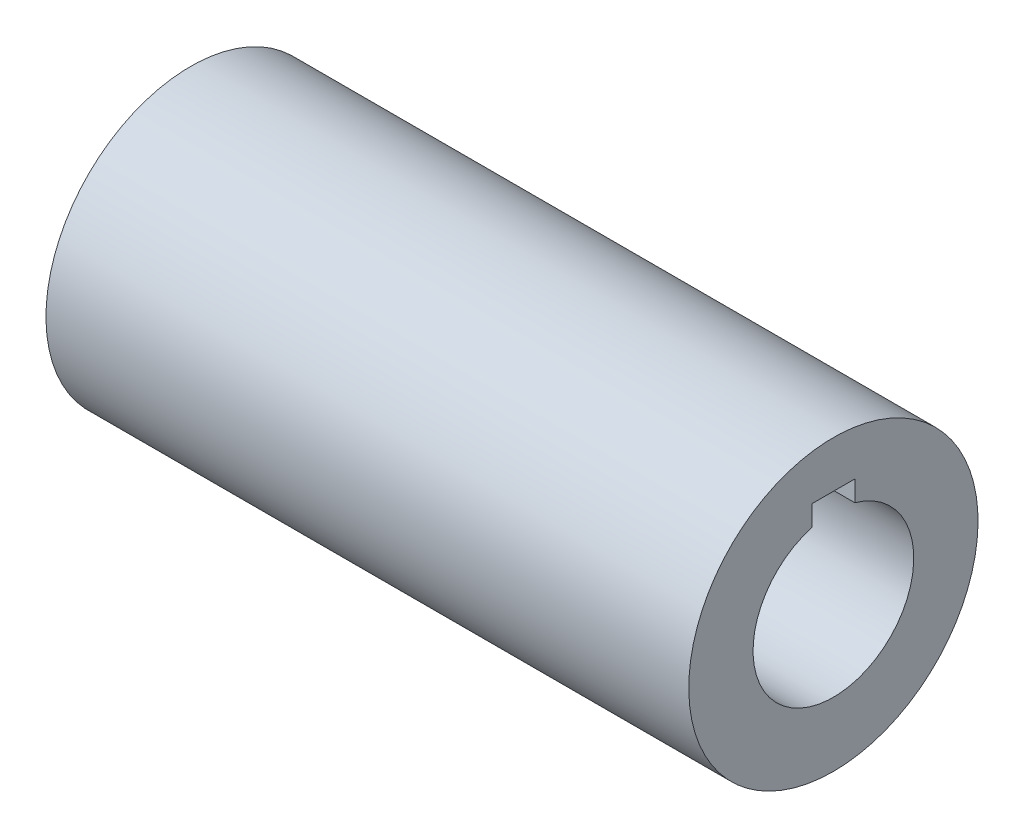
SolidWorks part; units mm, degrees
ref_plane "Ön Düzlem" through (0, 0, 0) normal (0, 0, 1) x (1, 0, 0)
ref_plane "Üst Düzlem" through (0, 0, 0) normal (0, 1, 0) x (1, 0, 0)
ref_plane "Sağ Düzlem" through (0, 0, 0) normal (1, 0, 0) x (0, 0, -1)
sketch "Sketch1" plane through (0, 0, 0) normal (0, 0, 1) x (1, 0, 0)
  line L0 (-60, 0) -> (60, 0) construction
  line L2 (-60, 15) -> (60, 15)
  line L3 (-60, 15) -> (-60, 27)
  line L4 (-60, 27) -> (60, 27)
  line L5 (60, 15) -> (60, 27)
  point P2 (0, 0)
  dimension "D1" = 120
  dimension "D2" = 15
  dimension "D3" = 12
revolve "Revolve1" add sketch "Sketch1" angle 360 about L0
sketch "Sketch2" plane through (0, 0, 0) normal (0, 1, 0) x (1, 0, 0)
  line L0 (-60, 27) -> (-60, -27) construction
  line L1 (-60, 4) -> (60, 4)
  line L2 (-60, 4) -> (-60, -4)
  line L3 (-60, -4) -> (60, -4)
  line L4 (60, 4) -> (60, -4)
  line L5 (60, -15) -> (60, 15) construction
  point P6 (60, -13.3815)
  point P9 (0, 4)
  point P11 (-60, 0)
  dimension "D1" = 8
extrude "Cut-Extrude1" cut sketch "Sketch2" along normal blind 18.3
